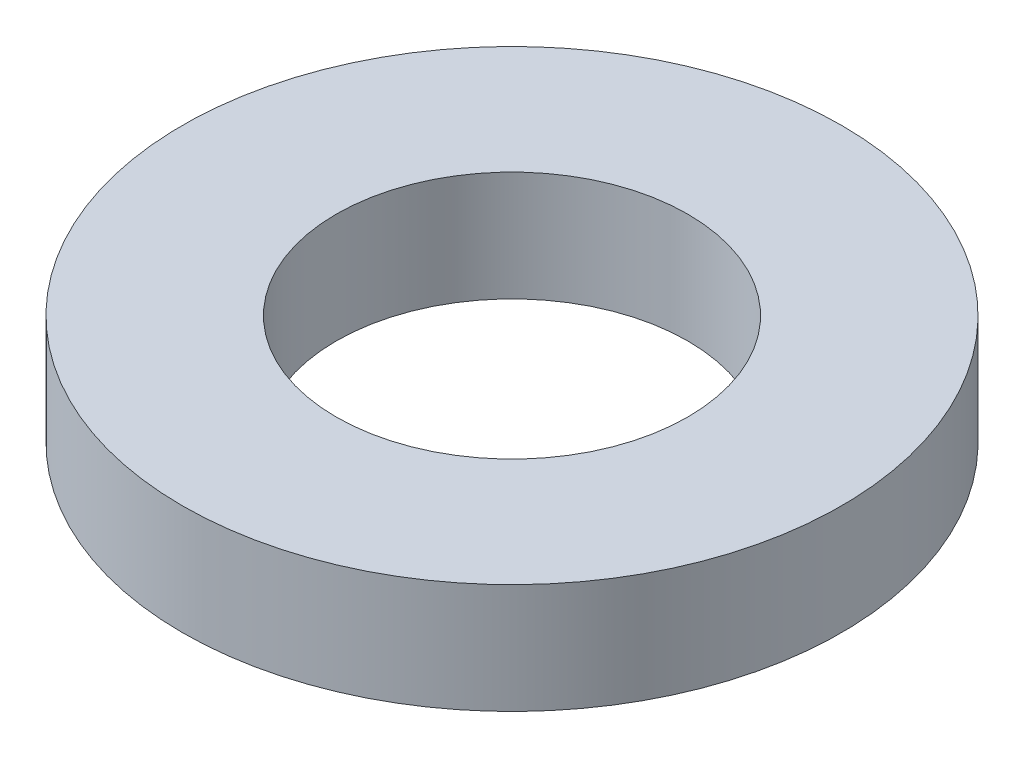
SolidWorks part; units mm, degrees
ref_plane "Front Plane" through (0, 0, 0) normal (0, 0, 1) x (1, 0, 0)
ref_plane "Top Plane" through (0, 0, 0) normal (0, 1, 0) x (1, 0, 0)
ref_plane "Right Plane" through (0, 0, 0) normal (1, 0, 0) x (0, 0, -1)
sketch "Sketch1" plane through (0, 0, 0) normal (0, 1, 0) x (1, 0, 0)
  circle A0 centre (0, 0) radius 4.7625
  circle A1 centre (0, 0) radius 2.54
  dimension "D1" = 9.525
  dimension "D2" = 5.08
extrude "Boss-Extrude1" add sketch "Sketch1" along normal blind 1.5875
